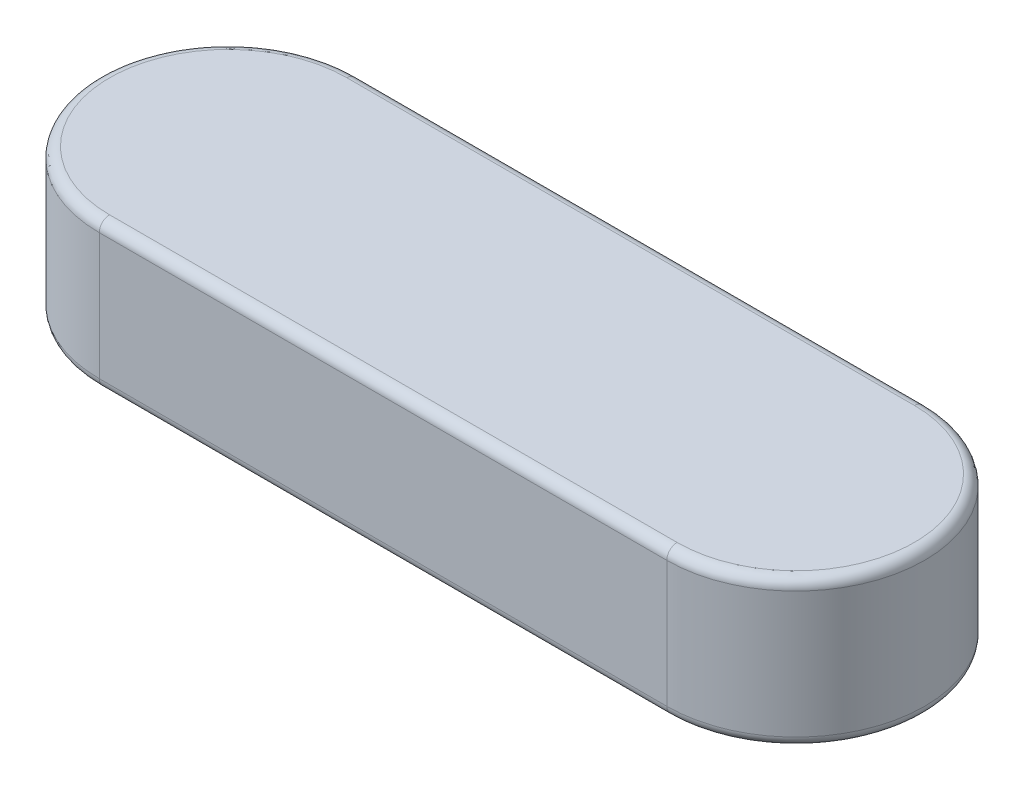
SolidWorks part; units mm, degrees
ref_plane "Front Plane" through (0, 0, 0) normal (0, 0, 1) x (1, 0, 0)
ref_plane "Top Plane" through (0, 0, 0) normal (0, 1, 0) x (1, 0, 0)
ref_plane "Right Plane" through (0, 0, 0) normal (1, 0, 0) x (0, 0, -1)
sketch "Sketch1" plane through (0, 0, 0) normal (0, 1, 0) x (1, 0, 0)
  line L1 (-22, 5) -> (0, 5)
  line L3 (-22, -5) -> (0, -5)
  arc A0 (0, -5) -> (0, 5) centre (0, 0) ccw
  arc A1 (-22, 5) -> (-22, -5) centre (-22, 0) ccw
  dimension "l" = 32
  dimension "b" = 10
extrude "Extrude1" add sketch "Sketch1" along normal blind 5.7
fillet "Fillet1" radius 0.4 8 edges at (-11, 0, -5) (5, 0, 0) (-27, 0, 0) (-11, 0, 5) (5, 5.7, 0) (-11, 5.7, 5) (-11, 5.7, -5) (-27, 5.7, 0)
